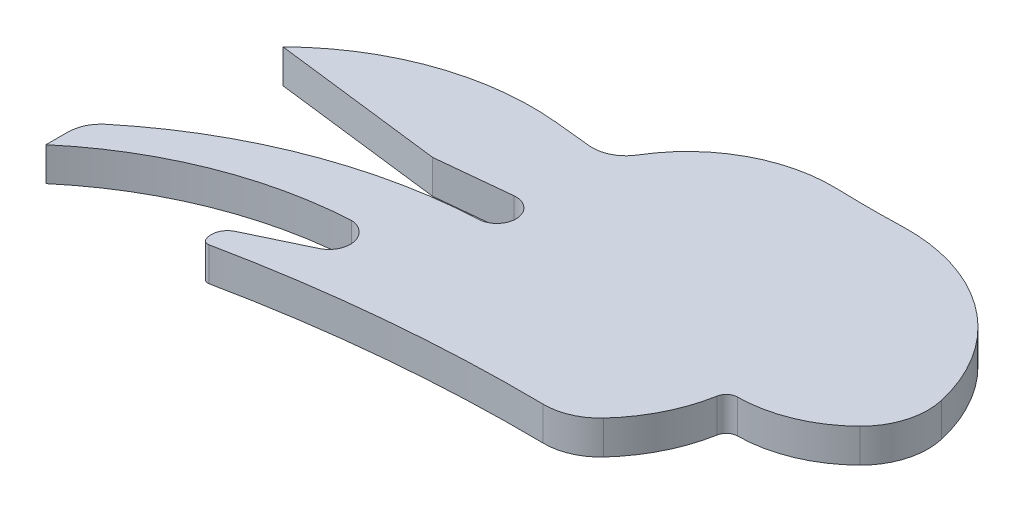
SolidWorks part; units mm, degrees
ref_plane "Front Plane" through (0, 0, 0) normal (0, 0, 1) x (1, 0, 0)
ref_plane "Top Plane" through (0, 0, 0) normal (0, 1, 0) x (1, 0, 0)
ref_plane "Right Plane" through (0, 0, 0) normal (1, 0, 0) x (0, 0, -1)
sketch "Sketch1" plane through (0, 0, 0) normal (0, 1, 0) x (1, 0, 0)
  line L0 (26.26, 24.39) -> (21.0032, 24.9261)
  line L1 (3, 18.6) -> (18.17, 16.74)
  line L2 (18.17, 16.74) -> (24.7397, 17.4014)
  line L3 (20.1225, 4.6688) -> (15.0925, 2.2682)
  line L4 (0, 0.53) -> (0, 3.83)
  line L5 (38.177, 32.3082) -> (44.8757, 32.3082)
  arc A0 (24.7397, 17.4014) -> (24.9912, 14.0119) centre (24.91, 15.71) cw
  arc A1 (14.63, 0) -> (44, 2.608) centre (40.3394, -122.8497) cw
  arc A2 (44, 2.608) -> (49.32, 11.86) centre (35.9268, 13.4057) ccw
  arc A3 (59.87, 17.72) -> (49.32, 11.86) centre (50.0588, 22.9567) cw
  arc A4 (41.4, 31.9) -> (59.87, 17.72) centre (44.8757, 17.3082) cw
  arc A5 (41.4, 31.9) -> (26.26, 24.39) centre (38.177, 19.3815) ccw
  arc A6 (21.0032, 24.9261) -> (3, 18.6) centre (18.7284, 2.6196) ccw
  arc A7 (0, 0.53) -> (19.42, 8.28) centre (21.2416, -24.4909) cw
  arc A8 (14.63, 0) -> (15.0925, 2.2682) centre (15.717, 0.9596) cw
  arc A9 (19.42, 8.28) -> (20.1225, 4.6688) centre (19.3042, 6.3835) cw
  arc A10 (0, 3.83) -> (24.9912, 14.0119) centre (26.9274, -26.5013) cw
  point P0 (41.4, 31.9)
  point P1 (59.87, 17.72)
  point P3 (49.32, 11.86)
  point P4 (24.91, 15.71)
  point P5 (18.17, 16.74)
  point P9 (14.63, 0)
  point P10 (0, 0.53)
  point P12 (44, 2.608)
  point P21 (26.26, 24.39)
  point P24 (3, 18.6)
  point P29 (19.42, 8.28)
  point P40 (21.6596, 25.117)
  point P42 (0, 0)
  point P43 (0, 0)
  point P44 (21.0032, 24.9261)
  point P45 (0, 0)
  point P46 (44, 2.608)
  dimension "D11" = 1.7
  dimension "D22" = 1.45
  dimension "D23" = 1.9
  dimension "D24" = 125.511
  dimension "D25" = 13.4821
  dimension "D26" = 11.1213
  dimension "D27" = 15
  dimension "D28" = 15.0925
  dimension "D29" = 22.4222
  dimension "D30" = 32.8214
  dimension "D31" = 40.5594
  dimension "D1" = 41.4
  dimension "D2" = 31.9
  dimension "D3" = 59.87
  dimension "D4" = 17.72
  dimension "D5" = 49.32
  dimension "D6" = 11.86
  dimension "D7" = 15.71
  dimension "D8" = 24.91
  dimension "D9" = 16.74
  dimension "D10" = 18.17
  dimension "D12" = 0.53
  dimension "D13" = 14.63
  dimension "D14" = 44
  dimension "D15" = 26.26
  dimension "D16" = 24.39
  dimension "D17" = 3
  dimension "D18" = 18.6
  dimension "D19" = 8.28
  dimension "D20" = 19.42
  dimension "D21" = 3.3
  dimension "D32" = 15.717
  dimension "D33" = 18.7284
  dimension "D34" = 29.292
extrude "Boss-Extrude1" add sketch "Sketch1" along normal blind 3 contours A10 A0 L2 L1 A6 L0 A5 A4 A3 A2 A1 A8 L3 A9 A7 L4
fillet "Fillet1" radius 6 1 edges at (59.87, 1.5, -17.72)
fillet "Fillet2" radius 90 1 edges at (41.4, 1.5, -31.9)
fillet "Fillet3" radius 3 2 edges at (0, 1.5, -3.83) (26.26, 1.5, -24.39)
fillet "Fillet4" radius 1 1 edges at (49.32, 1.5, -11.86)
fillet "Fillet5" radius 5 1 edges at (44, 1.5, -2.608)
fillet "Fillet7" radius 0.5 1 edges at (14.63, 1.5, 0)
